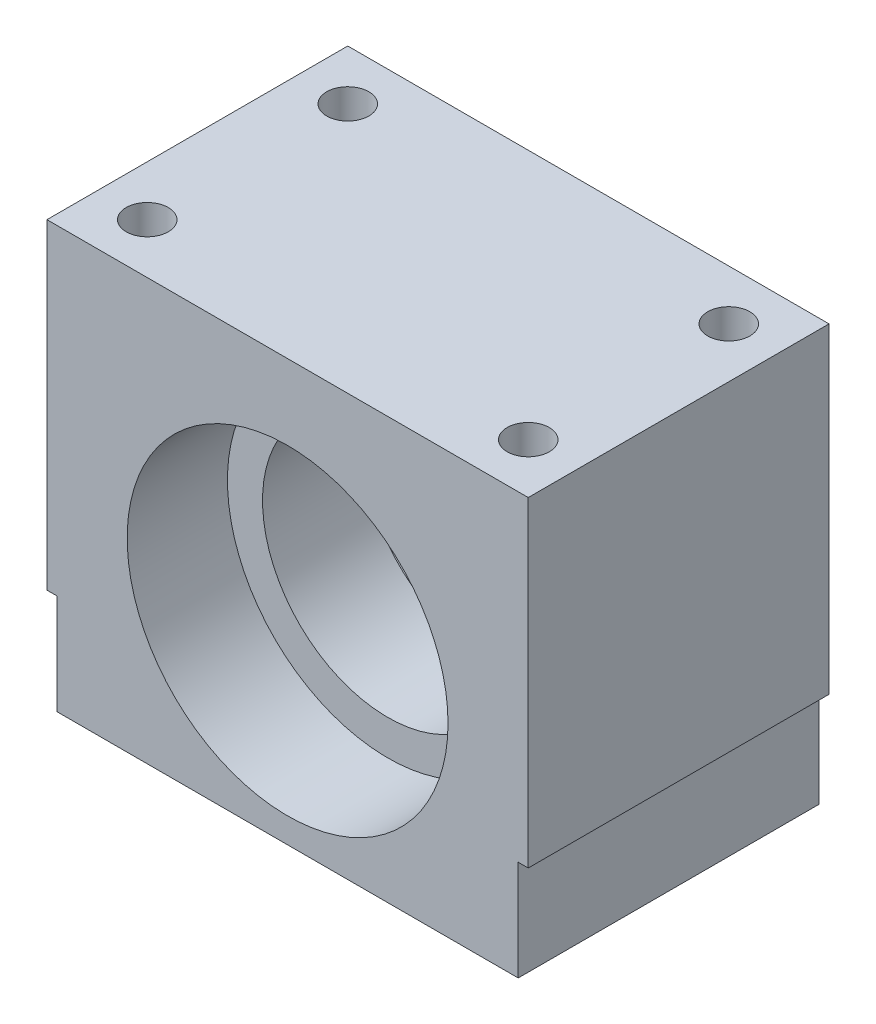
SolidWorks part; units mm, degrees
material "1.0037 (S235JR)"
ref_plane "Płaszczyzna przednia" through (0, 0, 0) normal (0, 0, 1) x (1, 0, 0)
ref_plane "Płaszczyzna górna" through (0, 0, 0) normal (0, 1, 0) x (1, 0, 0)
ref_plane "Płaszczyzna prawa" through (0, 0, 0) normal (1, 0, 0) x (0, 0, -1)
sketch "Szkic1" plane through (0, 0, 0) normal (0, 1, 0) x (1, 0, 0)
  line L1 (-24, -15) -> (24, -15)
  line L2 (-24, -15) -> (-24, 15)
  line L3 (-24, 15) -> (24, 15)
  line L4 (24, -15) -> (24, 15)
  line L5 (-24, -15) -> (24, 15) construction
  line L6 (-24, 15) -> (24, -15) construction
  point P0 (0, 0)
  dimension "D1" = 30
  dimension "D2" = 48
extrude "Dodanie-wyciągnięcie1" add sketch "Szkic1" along normal blind 42
sketch "Szkic3" plane through (0, 0, 15) normal (0, 0, 1) x (1, 0, 0)
  line L0 (0, 42) -> (0, 0) construction
  line L1 (-24, 42) -> (24, 42) construction
  line L2 (-24, 0) -> (24, 0) construction
  circle A0 centre (0, 18.5) radius 12.5
  dimension "D1" = 25
  dimension "D2" = 18.5
extrude "Wytnij-wyciągnięcie2" cut sketch "Szkic3" against normal through all
sketch "Szkic4" plane through (0, 0, 15) normal (0, 0, 1) x (1, 0, 0)
  circle A0 centre (0, 18.5) radius 16
  dimension "D1" = 32
extrude "Wytnij-wyciągnięcie3" cut sketch "Szkic4" against normal blind 10
mirror "Lustro1" about plane through (0, 0, 0) normal (0, 0, 1) of "Wytnij-wyciągnięcie3"
sketch "Szkic5" plane through (0, 42, 0) normal (0, 1, 0) x (1, 0, 0)
  line L8 (19, -10) -> (19, 10)
  line L9 (19, 10) -> (-19, 10)
  line L10 (-19, 10) -> (-19, -10)
  line L11 (-19, -10) -> (19, -10)
  line L12 (19, -10) -> (19, 10)
  line L13 (19, 10) -> (-19, 10)
  line L14 (-19, 10) -> (-19, -10)
  line L15 (-19, -10) -> (19, -10)
  dimension "D1" = 5
hole_wizard "Otwór gwintowany M5x0.81" positions "Szkic9" profile "Szkic6" tap size "M5x0.8" standard "Ansi Metric"
sketch "Szkic9" plane through (0, 42, 0) normal (0, 1, 0) x (1, 0, 0)
  point P0 (-19, -10)
  point P3 (-19, 10)
  point P6 (19, -10)
  point P9 (19, 10)
sketch "Szkic6" plane through (-19, 42, 10) normal (1, 0, 0) x (0, 0, 1)
  line L0 (0, 0) -> (0, 36.2618)
  line L1 (0, 36.2618) -> (2.1, 35)
  line L2 (2.1, 35) -> (2.1, 0)
  line L5 (2.1, 0) -> (0, 0)
  line L10 (0, 36.2618) -> (-2.1, 35) construction
  line L11 (0, -6.35) -> (0, 107.95) construction
  dimension "Średnica wiertła gwintu" = 4.2
  dimension "Głębokość otworu gwintowanego" = 35
  dimension "Kąt wiertła" = 118
sketch "Szkic10" plane through (0, 0, 15) normal (0, 0, 1) x (1, 0, 0)
  line L0 (24, 0) -> (24, 10)
  line L1 (24, 42) -> (24, 0) construction
  line L2 (24, 10) -> (23, 10)
  line L3 (23, 10) -> (23, 0)
  line L4 (-24, 0) -> (24, 0) construction
  line L5 (23, 0) -> (24, 0)
  line L6 (0, 0) -> (0, -6.2617) construction
  line L7 (-23, 0) -> (-24, 0)
  line L8 (-23, 10) -> (-23, 0)
  line L9 (-24, 10) -> (-23, 10)
  line L10 (-24, 0) -> (-24, 10)
  dimension "D1" = 10
  dimension "D2" = 1
extrude "Wytnij-wyciągnięcie4" cut sketch "Szkic10" against normal through all
